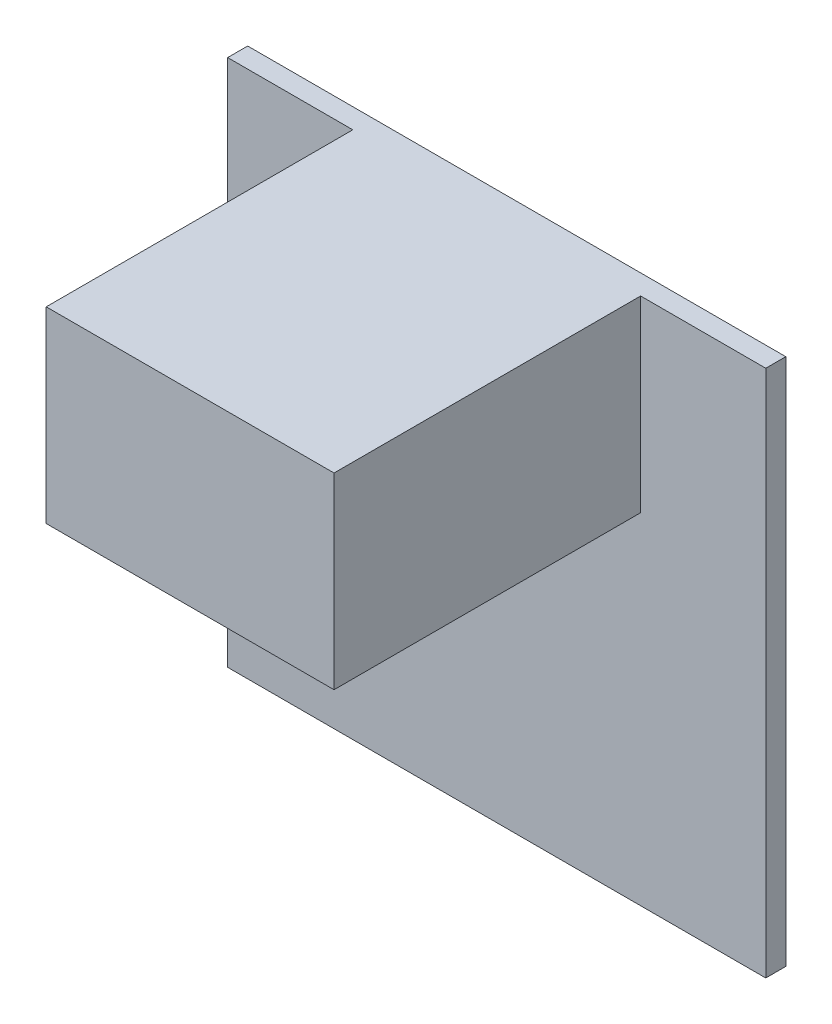
SolidWorks part; units mm, degrees
ref_plane "Front Plane" through (0, 0, 0) normal (0, 0, 1) x (1, 0, 0)
ref_plane "Top Plane" through (0, 0, 0) normal (0, 1, 0) x (1, 0, 0)
ref_plane "Right Plane" through (0, 0, 0) normal (1, 0, 0) x (0, 0, -1)
sketch "草图1" plane through (0, 0, 0) normal (0, 0, 1) x (1, 0, 0)
  line L1 (0, 0) -> (43, 0)
  line L2 (0, 0) -> (0, 42.2)
  line L3 (0, 42.2) -> (43, 42.2)
  line L4 (43, 0) -> (43, 42.2)
  dimension "D1" = 42.2
  dimension "D2" = 43
extrude "凸台-拉伸1" add sketch "草图1" along normal blind 1.6
sketch "草图2" plane through (0, 0, 1.6) normal (0, 0, 1) x (1, 0, 0)
  line L0 (21.5, 42.2) -> (21.5, -2.9) construction
  line L1 (43, 42.2) -> (0, 42.2) construction
  line L2 (43, 0) -> (43, 42.2) construction
  line L3 (10, 42.2) -> (33, 42.2)
  line L4 (10, 42.2) -> (10, 27.2)
  line L5 (10, 27.2) -> (33, 27.2)
  line L6 (33, 42.2) -> (33, 27.2)
  line L7 (0, 0) -> (43, 0)
  line L8 (0, 0) -> (0, 20)
  line L9 (0, 20) -> (43, 20)
  line L10 (43, 0) -> (43, 20)
  dimension "D1" = 23
  dimension "D2" = 11.5
  dimension "D3" = 15
  dimension "D4" = 20
extrude "凸台-拉伸3" add sketch "草图2" along normal blind 24.5 contours L4 L3 L6 L5
